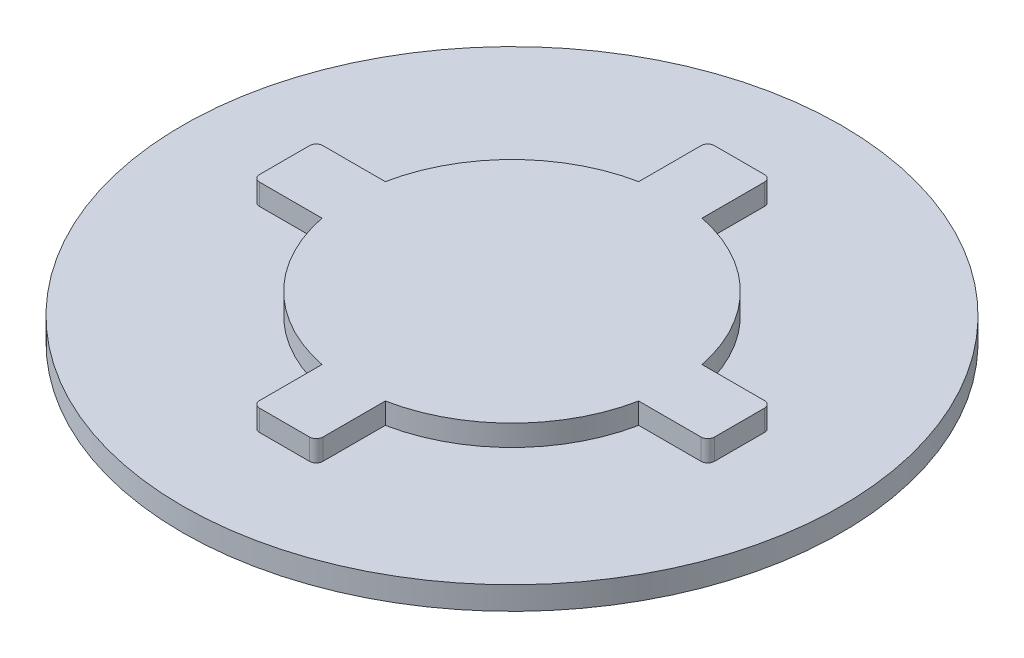
SolidWorks part; units mm, degrees
ref_plane "Alzado" through (0, 0, 0) normal (0, 0, 1) x (1, 0, 0)
ref_plane "Planta" through (0, 0, 0) normal (0, 1, 0) x (1, 0, 0)
ref_plane "Vista lateral" through (0, 0, 0) normal (1, 0, 0) x (0, 0, -1)
sketch "Croquis5" plane through (0, 0, 0) normal (0, 1, 0) x (1, 0, 0)
  circle A0 centre (0, 0) radius 24.5
  dimension "D1" = 49
extrude "Saliente-Extruir3" add sketch "Croquis5" along normal blind 3.2
sketch "Croquis6" plane through (0, 0, 0) normal (0, -1, 0) x (1, 0, 0)
  line L1 (33.5, 4.8) -> (-33.5, 4.8)
  line L2 (34.5, 3.8) -> (34.5, -3.8)
  line L3 (33.5, -4.8) -> (-33.5, -4.8)
  line L4 (-34.5, 3.8) -> (-34.5, -3.8)
  line L5 (34.5, 4.8) -> (-34.5, -4.8) construction
  line L6 (34.5, -4.8) -> (-34.5, 4.8) construction
  line L10 (3.8, -34.5) -> (-3.8, -34.5)
  line L11 (4.8, -33.5) -> (4.8, 33.5)
  line L12 (3.8, 34.5) -> (-3.8, 34.5)
  line L13 (-4.8, -33.5) -> (-4.8, 33.5)
  arc A0 (-3.8, -34.5) -> (-4.8, -33.5) centre (-3.8, -33.5) cw
  arc A1 (33.5, 4.8) -> (34.5, 3.8) centre (33.5, 3.8) cw
  arc A2 (34.5, -3.8) -> (33.5, -4.8) centre (33.5, -3.8) cw
  arc A3 (-33.5, -4.8) -> (-34.5, -3.8) centre (-33.5, -3.8) cw
  arc A4 (-33.5, 4.8) -> (-34.5, 3.8) centre (-33.5, 3.8) ccw
  arc A5 (4.8, -33.5) -> (3.8, -34.5) centre (3.8, -33.5) cw
  arc A6 (4.8, 33.5) -> (3.8, 34.5) centre (3.8, 33.5) ccw
  arc A7 (-4.8, 33.5) -> (-3.8, 34.5) centre (-3.8, 33.5) cw
  point P0 (0, 0)
  point P13 (0, 0)
  point P34 (0, 0)
  dimension "D4" = 1
  dimension "D1" = 69
  dimension "D2" = 9.6
extrude "Saliente-Extruir4" add sketch "Croquis6" against normal blind 3.2
sketch "Croquis7" plane through (0, 0, 0) normal (0, -1, 0) x (1, 0, 0)
  circle A0 centre (0, 0) radius 50
  dimension "D1" = 100
extrude "Saliente-Extruir5" add sketch "Croquis7" along normal blind 3.5
sketch "Croquis8" plane through (0, -3.5, 0) normal (0, -1, 0) x (1, 0, 0)
  line L0 (2.5, -25) -> (-2.5, -25)
  line L1 (25, 2.5) -> (-25, 2.5)
  line L2 (25, 2.5) -> (25, -2.5)
  line L3 (25, -2.5) -> (-25, -2.5)
  line L4 (-25, 2.5) -> (-25, -2.5)
  line L5 (25, 2.5) -> (-25, -2.5) construction
  line L6 (25, -2.5) -> (-25, 2.5) construction
  line L7 (2.5, -25) -> (2.5, 25)
  line L8 (2.5, 25) -> (-2.5, 25)
  line L9 (-2.5, -25) -> (-2.5, 25)
  circle A0 centre (0, 0) radius 15
  circle A1 centre (0, 0) radius 20
  point P0 (0, 0)
  point P13 (0, 0)
  dimension "D3" = 30
  dimension "D4" = 40
  dimension "D1" = 50
  dimension "D2" = 5
extrude "Cortar-Extruir3" cut sketch "Croquis8" against normal blind 3 contours A1 L9 L0 L7 | L9 A1 L7 A0 | L9 A0 L7 L3 | L9 L3 L7 L1 | L7 A0 L9 L1 | L7 A1 L9 A0 | A1 L7 L8 L9 | L3 A0 L1 L7 | L3 A1 L1 A0 | A1 L3 L2 L1 | L1 A0 L3 L9 | L1 A1 L3 A0 | A1 L1 L4 L3 | L9 A1 L1 A0 | L1 A1 L7 A0 | L7 A1 L3 A0 | L3 A1 L9 A0
sketch "Croquis9" plane through (0, -0.5, 0) normal (0, -1, 0) x (1, 0, 0)
  line L0 (-25, 0) -> (25, 0) construction
  line L1 (-25, 2.5) -> (-25, -2.5) construction
  line L2 (25, 2.5) -> (25, -2.5) construction
  line L3 (0, -25) -> (0, 25) construction
  line L4 (2.5, -25) -> (-2.5, -25) construction
  line L5 (2.5, 25) -> (-2.5, 25) construction
  circle A0 centre (0, 0) radius 22.5 construction
  circle A1 centre (0, 0) radius 3.5355
  dimension "D1" = 45
extrude "Cortar-Extruir4" cut sketch "Croquis9" against normal blind 2.5
sketch "Croquis10" plane through (0, -0.5, 0) normal (0, -1, 0) x (1, 0, 0)
  line L0 (-25, 0) -> (25, 0) construction
  line L1 (-25, 2.5) -> (-25, -2.5) construction
  line L2 (25, 2.5) -> (25, -2.5) construction
  line L3 (0, 25) -> (0, -25) construction
  line L4 (2.5, 25) -> (-2.5, 25) construction
  line L5 (2.5, -25) -> (-2.5, -25) construction
  circle A0 centre (0, 0) radius 22.5 construction
  circle A1 centre (-22.5, 0) radius 0.5
  circle A2 centre (0, 22.5) radius 0.5
  circle A3 centre (22.5, 0) radius 0.5
  circle A4 centre (0, -22.5) radius 0.5
  point P26 (0, 0)
  dimension "D1" = 45
  dimension "D2" = 1
  dimension "D3" = 4
extrude "Cortar-Extruir5" [suppressed] cut sketch "Croquis10" against normal blind 2
